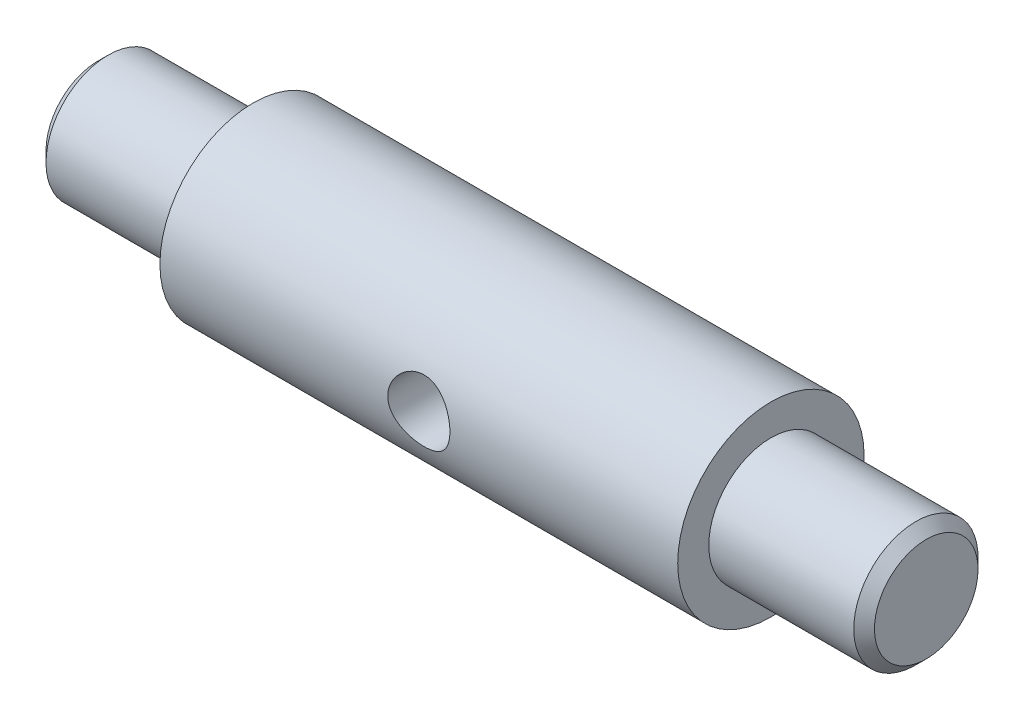
SolidWorks part; units mm, degrees
ref_plane "Front Plane" through (0, 0, 0) normal (0, 0, 1) x (1, 0, 0)
ref_plane "Top Plane" through (0, 0, 0) normal (0, 1, 0) x (1, 0, 0)
ref_plane "Right Plane" through (0, 0, 0) normal (1, 0, 0) x (0, 0, -1)
sketch "Sketch1" plane through (0, 0, 0) normal (0, 0, 1) x (1, 0, 0)
  line L0 (0, 0) -> (0, 6)
  line L1 (0, 6) -> (15, 6)
  line L2 (15, 6) -> (15, 9)
  line L3 (15, 9) -> (65, 9)
  line L4 (65, 9) -> (65, 6)
  line L5 (65, 6) -> (80, 6)
  line L6 (80, 6) -> (80, 0)
  line L7 (80, 0) -> (0, 0)
  dimension "D1" = 6
  dimension "D2" = 50
  dimension "D3" = 15
  dimension "D4" = 9
  dimension "D5" = 80
revolve "Revolve1" add sketch "Sketch1" angle 360 about L7
sketch "Sketch2" plane through (0, 0, 0) normal (0, 0, 1) x (1, 0, 0)
  line L0 (0, 6) -> (0, -6) construction
  circle A0 centre (40, 0) radius 3
  dimension "D1" = 6
  dimension "D2" = 40
extrude "Cut-Extrude2" cut sketch "Sketch2" against normal mid plane 50 contours A0
chamfer "Chamfer1" distance 1 angle 45 1 edges at (0, 6, 0)
chamfer "Chamfer2" distance 1 angle 45 1 edges at (80, 6, 0)
sketch "Sketch3" plane through (0, 0, 0) normal (-1, 0, 0) x (0, 0, 1)
  circle A0 centre (0, 0) radius 3
  dimension "D1" = 6
extrude "Cut-Extrude3" cut sketch "Sketch3" against normal blind 45
